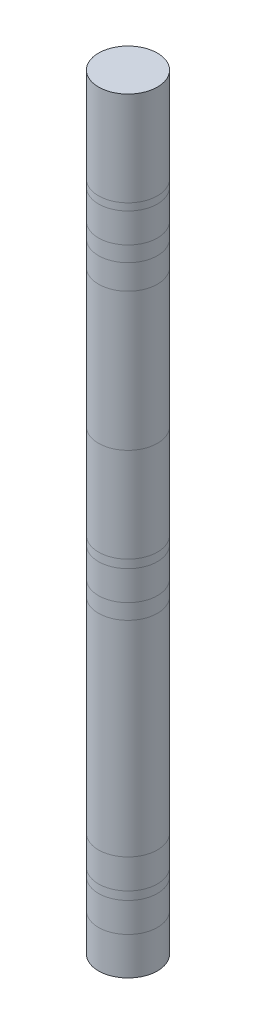
SolidWorks part; units mm, degrees
material "AISI 316 Annealed Stainless Steel Bar (SS)"
ref_plane "Front Plane" through (0, 0, 0) normal (0, 0, 1) x (1, 0, 0)
ref_plane "Top Plane" through (0, 0, 0) normal (0, 1, 0) x (1, 0, 0)
ref_plane "Right Plane" through (0, 0, 0) normal (1, 0, 0) x (0, 0, -1)
sketch "Sketch1" plane through (0, 0, 0) normal (0, 1, 0) x (1, 0, 0)
  circle A0 centre (0, 0) radius 6.35
  dimension "D1" = 12.7
extrude "Boss-Extrude1" add sketch "Sketch1" along normal blind 165.1
ref_plane "Plane1" through (0, 136.906, 0) normal (0, 1, 0) x (1, 0, 0)
ref_plane "Plane2" through (0, 133.604, 0) normal (0, 1, 0) x (1, 0, 0)
ref_plane "Plane3" through (0, 143.256, 0) normal (0, 1, 0) x (1, 0, 0)
ref_plane "Plane4" through (0, 144.78, 0) normal (0, 1, 0) x (1, 0, 0)
ref_plane "Plane5" through (0, 128.27, 0) normal (0, 1, 0) x (1, 0, 0)
ref_plane "Plane6" through (0, 98.552, 0) normal (0, 1, 0) x (1, 0, 0)
ref_plane "Plane7" through (0, 78.232, 0) normal (0, 1, 0) x (1, 0, 0)
ref_plane "Plane8" through (0, 76.454, 0) normal (0, 1, 0) x (1, 0, 0)
ref_plane "Plane9" through (0, 70.104, 0) normal (0, 1, 0) x (1, 0, 0)
ref_plane "Plane10" through (0, 66.802, 0) normal (0, 1, 0) x (1, 0, 0)
ref_plane "Plane11" through (0, 22.606, 0) normal (0, 1, 0) x (1, 0, 0)
ref_plane "Plane12" through (0, 16.256, 0) normal (0, 1, 0) x (1, 0, 0)
ref_plane "Plane13" through (0, 14.478, 0) normal (0, 1, 0) x (1, 0, 0)
ref_plane "Plane14" through (0, 8.128, 0) normal (0, 1, 0) x (1, 0, 0)
split line "Split Line2"
